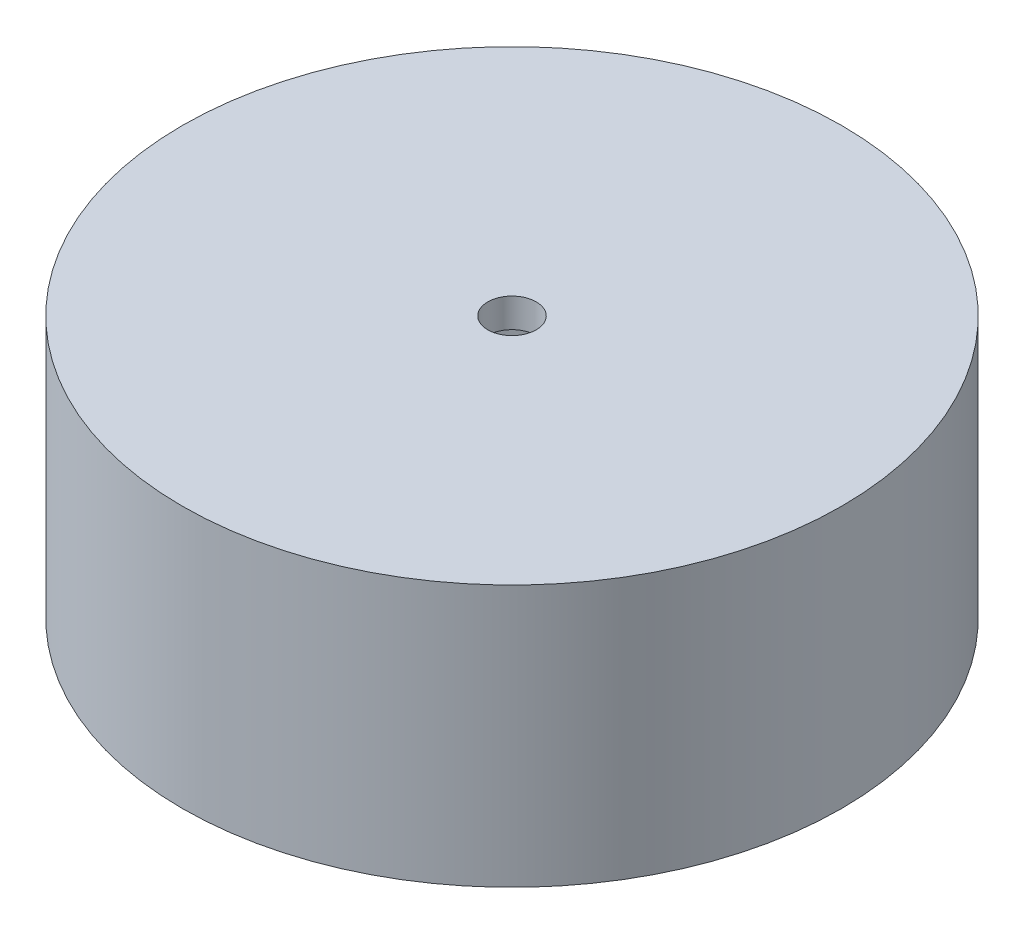
SolidWorks part; units mm, degrees
material "ABS"
ref_plane "Front Plane" through (0, 0, 0) normal (0, 0, 1) x (1, 0, 0)
ref_plane "Top Plane" through (0, 0, 0) normal (0, 1, 0) x (1, 0, 0)
ref_plane "Right Plane" through (0, 0, 0) normal (1, 0, 0) x (0, 0, -1)
sketch "Sketch1" plane through (0, 0, 0) normal (0, 1, 0) x (1, 0, 0)
  circle A0 centre (0, 0) radius 7
  circle A1 centre (0, 0) radius 8.5
  dimension "D1" = 14
  dimension "D2" = 1.5
extrude "Boss-Extrude1" add sketch "Sketch1" along normal blind 6
sketch "Sketch2" plane through (0, 6, 0) normal (0, 1, 0) x (1, 0, 0)
  circle A0 centre (0, 0) radius 8.5 construction
  circle A1 centre (0, 0) radius 8.5
extrude "Boss-Extrude2" add sketch "Sketch2" along normal blind 0.75
sketch "Sketch3" plane through (0, 6.75, 0) normal (0, 1, 0) x (1, 0, 0)
  circle A0 centre (0, 0) radius 0.625
  circle A1 centre (0, 0) radius 8.5
  circle A2 centre (0, 0) radius 8.5 construction
  dimension "D2" = 1.25
  dimension "D1" = 0
extrude "Cut-Extrude1" cut sketch "Sketch3" against normal through all both and the other way through all
fillet "Fillet1" radius 0.5 1 edges at (0, 0, 7)
